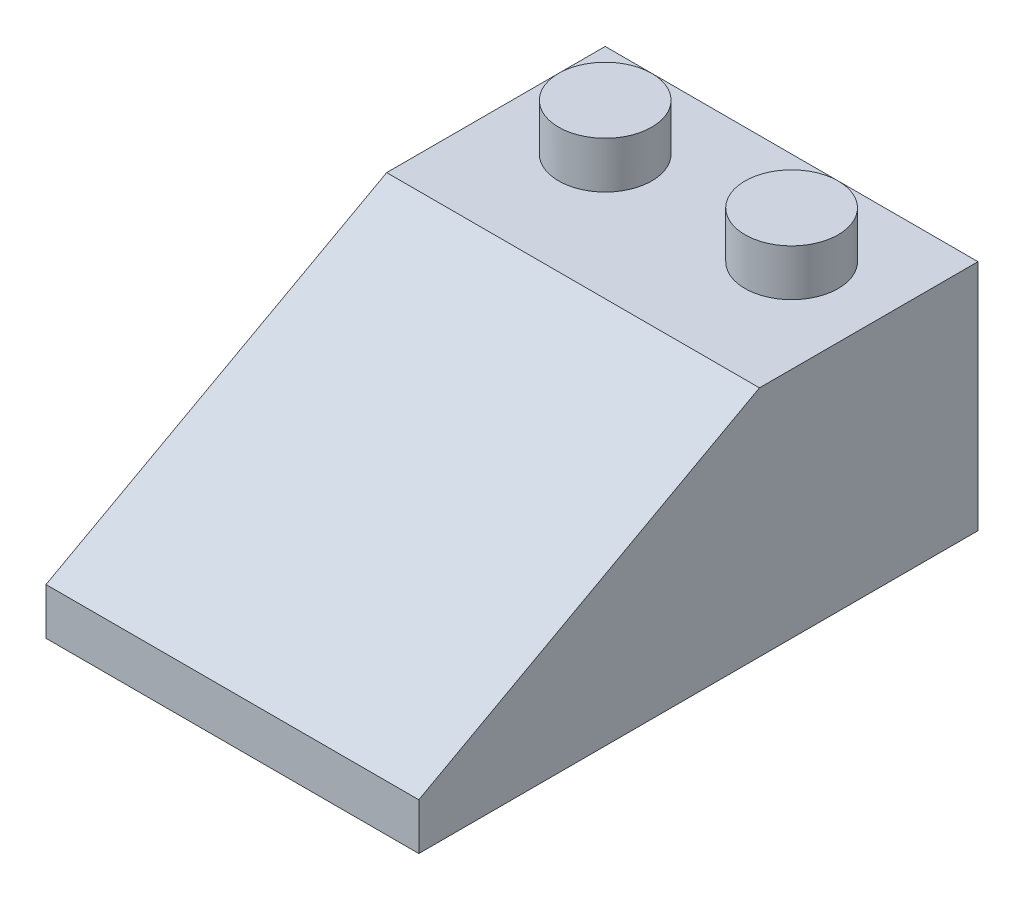
SolidWorks part; units mm, degrees
ref_plane "Front Plane" through (0, 0, 0) normal (0, 0, 1) x (1, 0, 0)
ref_plane "Top Plane" through (0, 0, 0) normal (0, 1, 0) x (1, 0, 0)
ref_plane "Right Plane" through (0, 0, 0) normal (1, 0, 0) x (0, 0, -1)
sketch "Sketch1" plane through (0, 0, 0) normal (1, 0, 0) x (0, 0, -1)
  line L0 (0, 0) -> (24, 0)
  line L1 (24, 0) -> (24, 10)
  line L2 (24, 10) -> (14.6207, 10)
  line L3 (14.6207, 10) -> (0, 2)
  line L4 (0, 2) -> (0, 0)
  dimension "D1" = 10
  dimension "D2" = 24
  dimension "D3" = 9.3793
  dimension "D4" = 2
extrude "Boss-Extrude1" add sketch "Sketch1" along normal blind 16
sketch "Sketch2" plane through (0, 10, 0) normal (0, 1, 0) x (1, 0, 0)
  line L0 (8, 24) -> (8, 15.3254) construction
  line L1 (16, 24) -> (0, 24) construction
  line L2 (0, 24) -> (0, 14.6207) construction
  circle A0 centre (4, 20) radius 2
  circle A1 centre (12, 20) radius 2
  point P8 (1.2928, 18.7714)
  point P9 (3.3604, 19.6673)
  dimension "D1" = 4
  dimension "D2" = 4
  dimension "D3" = 4
extrude "Boss-Extrude2" add sketch "Sketch2" along normal blind 2
shell "Shell1" thickness 1
sketch "Sketch3" plane through (0, 0, 0) normal (0, -1, 0) x (1, 0, 0)
  line L0 (1.2389, -12) -> (14.1959, -12) construction
  line L1 (16, -24) -> (0, -24) construction
  line L3 (16, 0) -> (0, 0) construction
  line L4 (0, 0) -> (0, -24) construction
  circle A0 centre (8, -8) radius 2.7
  circle A1 centre (8, -8) radius 1.7
  circle A2 centre (8, -16) radius 2.7
  circle A3 centre (8, -16) radius 1.7
  point P9 (0, 0)
  dimension "D2" = 3.4
  dimension "D3" = 5.4
  dimension "D1" = 12
  dimension "D4" = 8
  dimension "D5" = 8
extrude "Boss-Extrude3" add sketch "Sketch3" against normal up to next
